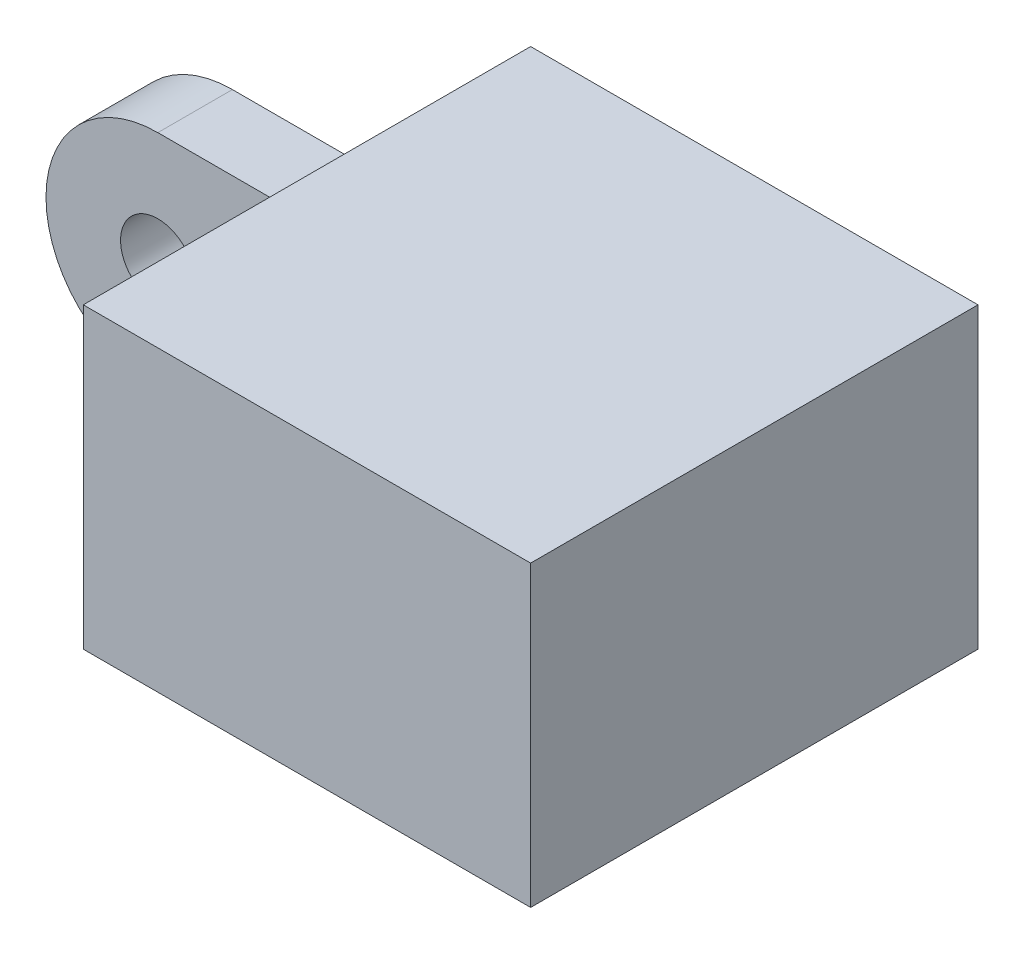
SolidWorks part; units mm, degrees
ref_plane "Front Plane" through (0, 0, 0) normal (0, 0, 1) x (1, 0, 0)
ref_plane "Top Plane" through (0, 0, 0) normal (0, 1, 0) x (1, 0, 0)
ref_plane "Right Plane" through (0, 0, 0) normal (1, 0, 0) x (0, 0, -1)
sketch "Sketch1" plane through (0, 0, 0) normal (0, 0, 1) x (1, 0, 0)
  line L0 (-30, -15) -> (-30, -20)
  line L1 (-30, 20) -> (30, 20)
  line L2 (-30, 20) -> (-30, 15)
  line L3 (-30, -20) -> (30, -20)
  line L4 (30, 20) -> (30, -20)
  line L5 (-30, 20) -> (30, -20) construction
  line L6 (-30, -20) -> (30, 20) construction
  line L7 (-50, 15) -> (-30, 15)
  line L8 (-50, -15) -> (-30, -15)
  arc A0 (-50, 15) -> (-50, -15) centre (-50, 0) ccw
  circle A1 centre (-50, 0) radius 5
  point P0 (0, 0)
  dimension "D3" = 30
  dimension "D4" = 10
  dimension "D1" = 40
  dimension "D2" = 60
extrude "Boss-Extrude1" add sketch "Sketch1" along normal blind 10
sketch "Sketch2" plane through (0, 0, 10) normal (0, 0, 1) x (1, 0, 0)
  line L0 (-30, 20) -> (-30, -20)
  line L1 (-30, -20) -> (30, -20)
  line L2 (30, -20) -> (30, 20)
  line L3 (30, 20) -> (-30, 20)
extrude "Boss-Extrude2" add sketch "Sketch2" along normal blind 30
sketch "Sketch3" plane through (0, 0, 0) normal (0, 0, -1) x (-1, 0, 0)
  line L0 (-30, 20) -> (-30, -20)
  line L1 (-30, -20) -> (30, -20)
  line L2 (30, -20) -> (30, 20)
  line L3 (30, 20) -> (-30, 20)
extrude "Boss-Extrude3" add sketch "Sketch3" along normal blind 20
